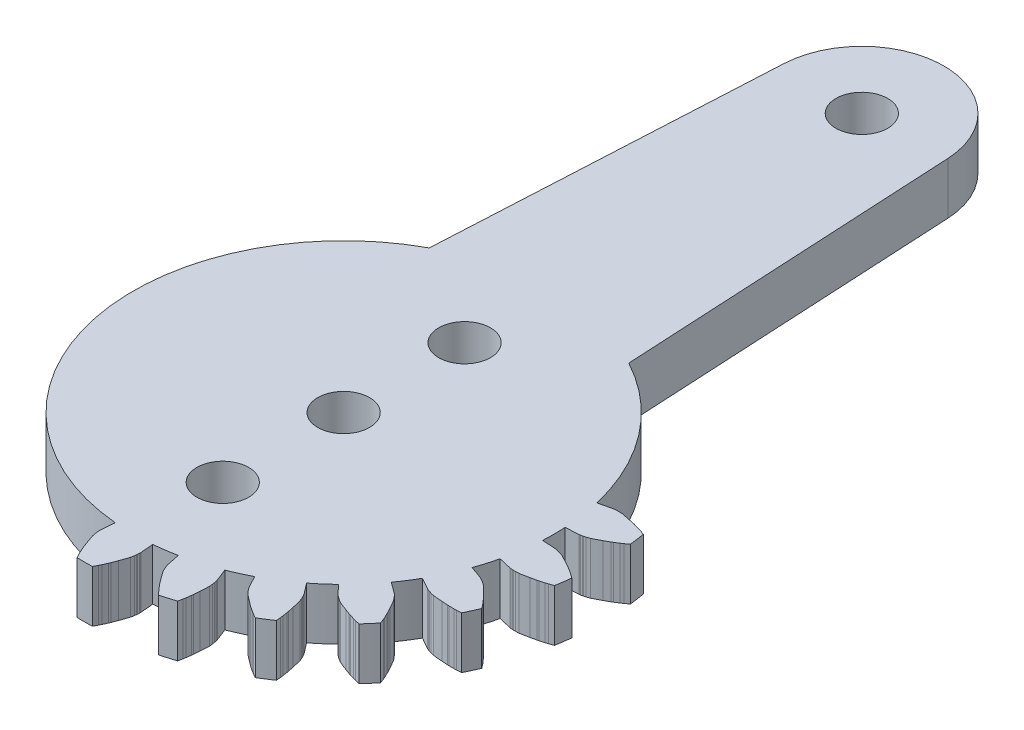
SolidWorks part; units mm, degrees
material "普通碳钢"
ref_plane "前视" through (0, 0, 0) normal (0, 0, 1) x (1, 0, 0)
ref_plane "上视" through (0, 0, 0) normal (0, 1, 0) x (1, 0, 0)
ref_plane "右视" through (0, 0, 0) normal (1, 0, 0) x (0, 0, -1)
sketch "草图1" plane through (0, 0, 0) normal (0, 1, 0) x (1, 0, 0)
  line L0 (39.751, 40.5224) -> (39.6866, 41.2679)
  line L1 (39.6866, 41.2679) -> (39.6851, 41.3287)
  line L2 (39.6851, 41.3287) -> (39.6859, 41.3577)
  line L3 (39.6859, 41.3577) -> (39.6916, 41.4528)
  line L4 (39.6916, 41.4528) -> (39.6929, 41.4698)
  line L5 (39.6929, 41.4698) -> (39.6966, 41.5042)
  line L6 (39.6966, 41.5042) -> (39.712, 41.6258)
  line L7 (39.712, 41.6258) -> (39.7121, 41.6267)
  line L8 (39.7121, 41.6267) -> (39.7482, 41.8247)
  line L9 (39.9295, 42.3366) -> (40.044, 42.6442)
  line L10 (40.044, 42.6442) -> (40.0454, 42.6478)
  line L11 (40.0454, 42.6478) -> (40.0855, 42.7398)
  line L12 (40.0855, 42.7398) -> (40.1995, 42.9971)
  line L13 (41.9203, 40.5224) -> (41.9848, 41.2679)
  line L14 (41.9848, 41.2679) -> (41.9862, 41.3287)
  line L15 (41.9862, 41.3287) -> (41.9855, 41.3577)
  line L16 (41.9855, 41.3577) -> (41.9797, 41.4528)
  line L17 (41.9797, 41.4528) -> (41.9784, 41.4698)
  line L18 (41.9784, 41.4698) -> (41.9748, 41.5042)
  line L19 (41.9748, 41.5042) -> (41.9594, 41.6258)
  line L20 (41.9594, 41.6258) -> (41.9592, 41.6267)
  line L21 (41.9592, 41.6267) -> (41.9231, 41.8247)
  line L22 (41.7419, 42.3366) -> (41.6274, 42.6442)
  line L23 (41.6274, 42.6442) -> (41.626, 42.6478)
  line L24 (41.626, 42.6478) -> (41.5858, 42.7398)
  line L25 (41.5858, 42.7398) -> (41.4718, 42.9971)
  circle A0 centre (40.8357, 28.3833) radius 12.1875 construction
  arc A1 (39.751, 40.5224) -> (41.9203, 40.5224) centre (40.8357, 28.3833) cw
  arc A2 (41.9231, 41.8247) -> (41.7419, 42.3366) centre (25.8953, 36.4382) ccw
  arc A4 (39.9295, 42.3366) -> (39.7482, 41.8247) centre (55.7761, 36.4382) ccw
  arc A5 (40.2653, 43.1347) -> (40.1995, 42.9971) centre (42.6892, 41.8899) ccw
  arc A6 (40.3945, 43.3768) -> (40.2653, 43.1347) centre (48.1168, 39.1026) ccw
  arc A11 (41.4718, 42.9971) -> (41.406, 43.1347) centre (38.9822, 41.8899) ccw
  arc A12 (41.406, 43.1347) -> (41.2769, 43.3768) centre (33.5546, 39.1026) ccw
  arc A13 (41.2769, 43.3768) -> (40.3945, 43.3768) centre (40.8357, 28.3833) ccw
  dimension "D1" = 24.375
extrude "凸台-拉伸1" add sketch "草图1" along normal blind 3 contours A4 L8 L7 L6 L5 L4 L3 L2 L1 L0 A1 L13 L14 L15 L16 L17 L18 L19 L20 L21 A2 L22 L23 L24 L25 A11 A12 A13 A6 A5 L12 L11 L10 L9
sketch "草图2" plane through (0, 0, 0) normal (0, -1, 0) x (1, 0, 0)
  circle A0 centre (40.8357, -28.3833) radius 12.1875
  circle A1 centre (40.8357, -28.3833) radius 1.5
  circle A2 centre (40.8357, -28.3833) radius 7 construction
  circle A3 centre (40.8357, -21.3833) radius 1.5
  circle A4 centre (40.8357, -35.3833) radius 1.5
  dimension "D1" = 3
  dimension "D2" = 24.375
  dimension "D3" = 14
  dimension "D4" = 3
  dimension "D5" = 3
extrude "凸台-拉伸2" add sketch "草图2" against normal blind 3
pattern_circular "阵列(圆周)2" count 22 over 360 about axis through (40.8357, 0, -28.3833) along (0, 1, 0) of "凸台-拉伸1"
sketch "草图3" plane through (0, 0, 0) normal (0, -1, 0) x (-1, 0, 0)
  circle A0 centre (-40.8357, 28.3833) radius 13.75
  dimension "D1" = 27.5
sketch "草图5" plane through (0, 0, 0) normal (0, -1, 0) x (1, 0, 0)
  line L0 (40.8357, -19.8833) -> (40.8357, -63.1398) construction
  line L1 (45.5857, -58.6327) -> (46.6107, -39.1157)
  line L2 (36.0857, -58.6327) -> (35.0607, -39.1157)
  circle A0 centre (40.8357, -21.3833) radius 1.5 construction
  circle A2 centre (40.8357, -28.3833) radius 12.1875 construction
  arc A3 (53.0056, -29.0373) -> (53.0056, -27.7293) centre (40.8357, -28.3833) ccw construction
  arc A4 (36.0857, -58.6327) -> (45.5857, -58.6327) centre (40.8357, -58.3833) ccw
  circle A5 centre (40.8357, -58.3833) radius 1.5
  arc A6 (35.0607, -39.1157) -> (46.6107, -39.1157) centre (40.8357, -28.3833) ccw
  dimension "D4" = 3
  dimension "D1" = 11.55
  dimension "D2" = 9.5
  dimension "D3" = 30
extrude "凸台-拉伸3" add sketch "草图5" against normal blind 3
sketch "草图7" plane through (0, 0, 0) normal (0, -1, 0) x (1, 0, 0)
  line L0 (36.0857, -58.6327) -> (34.9723, -37.4337) construction
  line L1 (35.0751, -39.3907) -> (36.0857, -58.6327) construction
  line L2 (45.5857, -58.6327) -> (46.7591, -36.2892) construction
  line L3 (45.5857, -58.6327) -> (46.5962, -39.3907) construction
  line L4 (35.0607, -39.1157) -> (35.0751, -39.3907)
  line L5 (35.0751, -39.3907) -> (34.8365, -39.8437)
  line L6 (34.8365, -39.8437) -> (33.6211, -45.0698)
  line L7 (33.6211, -45.0698) -> (23.2947, -35.4215)
  line L8 (23.2947, -35.4215) -> (25.1891, -22.1682)
  line L9 (25.1891, -22.1682) -> (31.4308, -11.204)
  line L10 (31.4308, -11.204) -> (37.9696, -9.817)
  line L11 (37.9696, -9.817) -> (39.751, -16.2441)
  line L12 (46.6107, -39.1157) -> (46.5962, -39.3907)
  line L13 (46.5962, -39.3907) -> (47.0142, -42.3632)
  line L14 (52.3284, -32.4394) -> (55.4375, -32.4394)
  line L15 (55.4375, -32.4394) -> (53.5277, -41.7128)
  line L16 (53.5277, -41.7128) -> (47.0142, -42.3632)
  arc A0 (35.0607, -39.1157) -> (39.751, -16.2441) centre (40.8357, -28.3833) cw
  circle A1 centre (40.8357, -28.3833) radius 1.5 construction
  circle A2 centre (40.8357, -28.3833) radius 12.1875 construction
  arc A3 (46.6107, -39.1157) -> (52.3284, -32.4394) centre (40.8357, -28.3833) ccw
extrude "切除-拉伸1" cut sketch "草图7" against normal blind 3
sketch "草图8" plane through (0, 0, 0) normal (0, -1, 0) x (-1, 0, 0)
  line L0 (-40.8357, 35.3833) -> (-40.8357, 21.3833)
